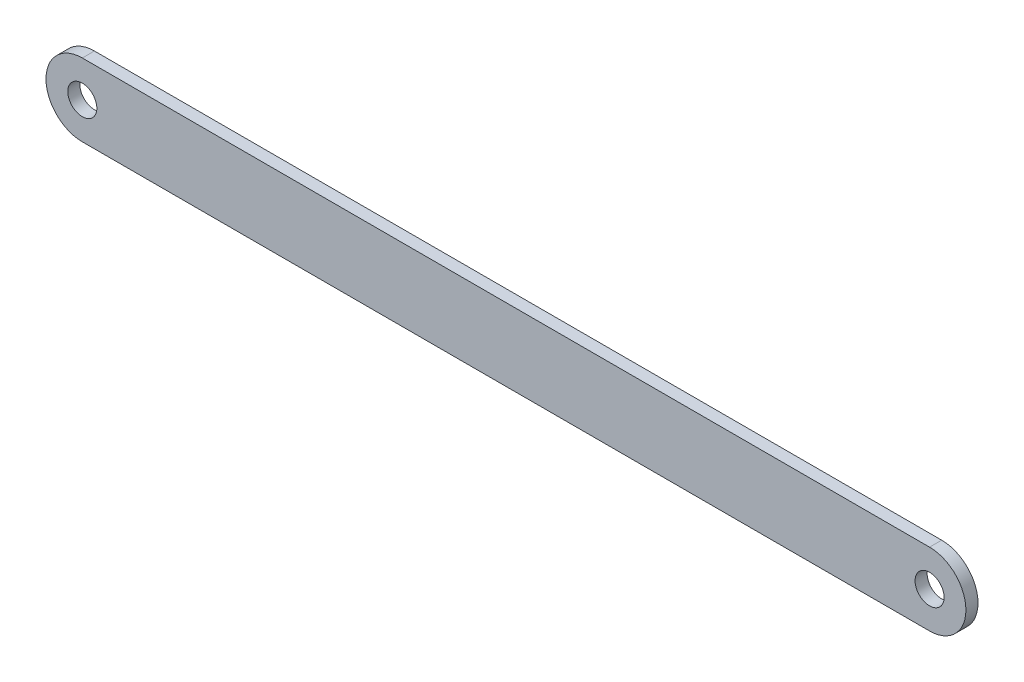
SolidWorks part; units mm, degrees
ref_plane "Front Plane" through (0, 0, 0) normal (0, 0, 1) x (1, 0, 0)
ref_plane "Top Plane" through (0, 0, 0) normal (0, 1, 0) x (1, 0, 0)
ref_plane "Right Plane" through (0, 0, 0) normal (1, 0, 0) x (0, 0, -1)
sketch "Sketch1" plane through (0, 0, 0) normal (0, 0, 1) x (1, 0, 0)
  line L0 (0, 0) -> (350, 0) construction
  line L1 (0, 15) -> (350, 15)
  line L2 (0, -15) -> (350, -15)
  arc A0 (0, 15) -> (0, -15) centre (0, 0) ccw
  arc A1 (350, -15) -> (350, 15) centre (350, 0) ccw
  circle A2 centre (0, 0) radius 6
  circle A3 centre (350, 0) radius 6
  point P3 (175, 0)
  dimension "D2" = 12
  dimension "D1" = 350
extrude "Boss-Extrude1" add sketch "Sketch1" along normal blind 5
sketch "Sketch3" [suppressed] plane through (0, 0, 5) normal (0, 0, 1) x (1, 0, 0)
  line L0 (40, 15) -> (40, -37.2706)
  line L1 (320, 15) -> (0, 15) construction
  line L3 (80.1893, -65.4872) -> (220, -15)
  line L4 (0, -15) -> (320, -15) construction
  line L6 (220, -15) -> (220, 15)
  line L7 (220, 15) -> (40, 15)
  arc A0 (40, -37.2706) -> (80.1893, -65.4872) centre (70, -37.2706) ccw
  circle A1 centre (70, -37.2706) radius 6
  circle A2 centre (320, 0) radius 6 construction
  circle A3 centre (320, 0) radius 6 construction
  circle A4 centre (0, 0) radius 6 construction
  point P19 (40, -80)
  dimension "D3" = 180
  dimension "D4" = 30
  dimension "D1" = 95
  dimension "D2" = 40
extrude "Boss-Extrude2" [suppressed] add sketch "Sketch3" along normal blind 2.5 separate body
sketch "Sketch5" [suppressed] plane through (0, 0, 7.5) normal (0, 0, -1) x (-1, 0, 0)
  circle A0 centre (-110, -45.2706) radius 5
  dimension "D1" = 40
  dimension "D3" = 10
  dimension "D2" = 8
extrude "Boss-Extrude3" [suppressed] add sketch "Sketch5" against normal blind 2.5
ref_plane "Plane1" [suppressed] through (0, 0, 2.5) normal (0, 0, 1) x (1, 0, 0)
mirror "Mirror2" [suppressed] about plane through (0, 0, 2.5) normal (0, 0, 1)
delete or keep bodies "Body-Delete1" [suppressed] type delete bodies bodies 103 102
